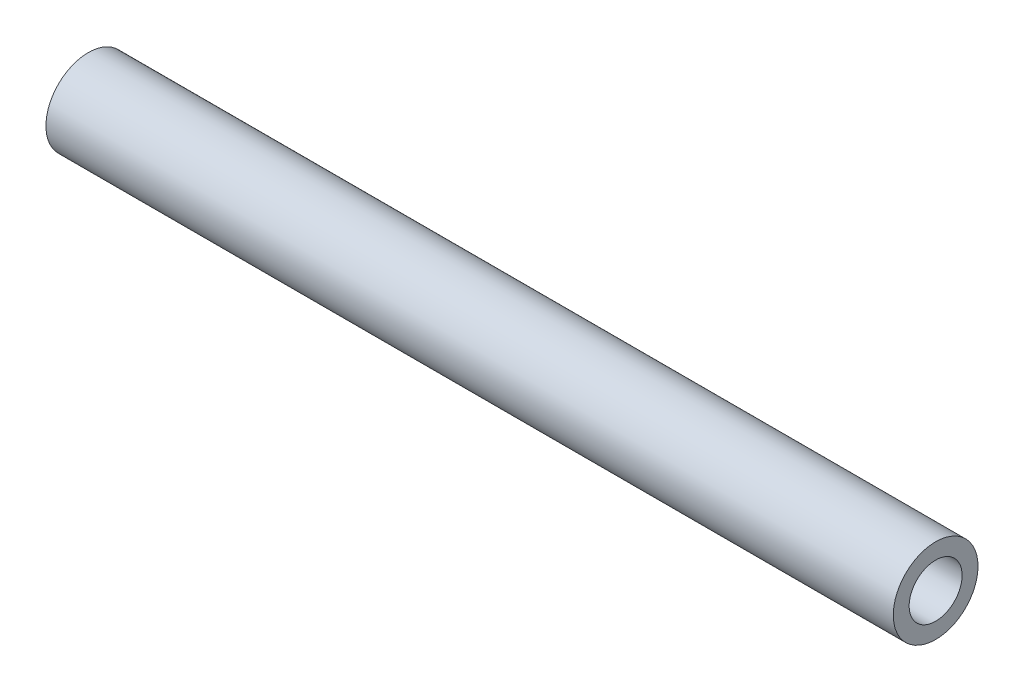
SolidWorks part; units mm, degrees
material "6061 Alloy"
ref_plane "Front Plane" through (0, 0, 0) normal (0, 0, 1) x (1, 0, 0)
ref_plane "Top Plane" through (0, 0, 0) normal (0, 1, 0) x (1, 0, 0)
ref_plane "Right Plane" through (0, 0, 0) normal (1, 0, 0) x (0, 0, -1)
sketch "Sketch1" plane through (0, 0, 0) normal (1, 0, 0) x (0, 0, -1)
  circle A0 centre (0, 0) radius 6.35
  circle A1 centre (0, 0) radius 3.9688
  dimension "D1" = 7.9375
  dimension "D2" = 12.7
extrude "Extrude1" add sketch "Sketch1" along normal blind 127
